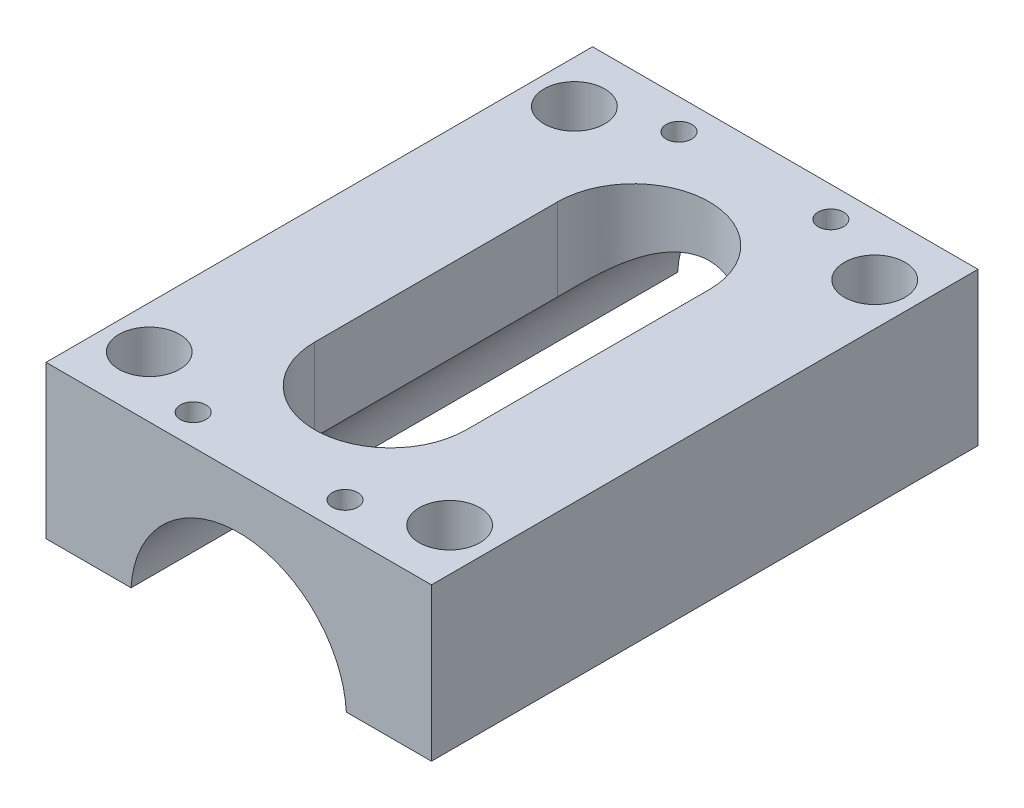
SolidWorks part; units mm, degrees
ref_plane "Front" through (0, 0, 0) normal (0, 0, 1) x (1, 0, 0)
ref_plane "Top" through (0, 0, 0) normal (0, 1, 0) x (1, 0, 0)
ref_plane "Right" through (0, 0, 0) normal (1, 0, 0) x (0, 0, -1)
sketch "Sketch1" plane through (0, 0, 0) normal (0, 0, 1) x (1, 0, 0)
  line L0 (-31.75, 0) -> (31.75, 0) construction
  line L1 (-31.7342, 1) -> (-17.7218, 1)
  line L2 (-31.75, 1) -> (31.75, 1) construction
  line L3 (17.7218, 1) -> (31.7342, 1)
  arc A0 (31.7342, 1) -> (-31.7342, 1) centre (0, 0) ccw
  arc A1 (17.7218, 1) -> (-17.7218, 1) centre (0, 0) ccw
  dimension "D1" = 35.5
  dimension "D2" = 63.5
  dimension "D3" = 1
extrude "Boss-Extrude1" add sketch "Sketch1" along normal blind 90
sketch "Sketch12" plane through (0, 0, 90) normal (0, 0, 1) x (1, 0, 0)
  line L2 (-31.7342, 1) -> (-31.7342, 31.75)
  line L3 (-31.7342, 31.75) -> (31.7342, 31.75)
  line L4 (31.7342, 1) -> (31.7342, 31.75)
  arc A0 (31.7342, 1) -> (-31.7342, 1) centre (0, 0) ccw construction
  arc A1 (31.7342, 1) -> (-31.7342, 1) centre (0, 0) ccw
  point P4 (0, 16.375)
  point P9 (0, 0)
  arc M5 (31.7342, 1) -> (-31.7342, 1) centre (0, 0) ccw
extrude "Boss-Extrude2" add sketch "Sketch12" against normal up to surface (90 mm away) contours L4 L3 M5 | L3 L2 M5 up to face at (0, 12.875, 0)
sketch "Sketch2" plane through (0, 1, 0) normal (0, -1, 0) x (-1, 0, 0)
  line L0 (24.728, -90) -> (24.728, 0) construction
  line L1 (31.7342, -90) -> (17.7218, -90) construction
  line L2 (31.7342, 0) -> (17.7218, 0) construction
  line L3 (-24.728, -90) -> (-24.728, 0) construction
  line L4 (-17.7218, -90) -> (-31.7342, -90) construction
  line L5 (-17.7218, 0) -> (-31.7342, 0) construction
  line L6 (0, -90) -> (0, 0) construction
  line L7 (-17.7218, -90) -> (17.7218, -90) construction
  circle A0 centre (24.728, -80) radius 1
  circle A1 centre (24.728, -10) radius 1
  circle A2 centre (-24.728, -10) radius 1
  circle A3 centre (-24.728, -80) radius 1
  dimension "D1" = 10
  dimension "D2" = 10
  dimension "D3" = 2
hole_wizard "Ø5.0mm Clearance Dowel Hole1" positions "3DSketch1" profile "Sketch3" hole size "Ø5.0" standard "ANSI Metric" end condition up to next
sketch3d "3DSketch1"
  point P0 (-24.728, 1, 80)
  point P3 (-24.728, 1, 10)
  point P6 (24.728, 1, 80)
  point P9 (24.728, 1, 10)
sketch "Sketch3" plane through (-24.728, 1, 80) normal (1, 0, 0) x (0, 0, -1)
  line L0 (0, 0) -> (0, 30.75)
  line L1 (0, 30.75) -> (2.5, 30.75)
  line L2 (2.5, 30.75) -> (2.5, 0)
  line L5 (2.5, 0) -> (0, 0)
  line L11 (0, -6.35) -> (0, 107.95) construction
  dimension "Thru Hole Dia." = 5
  dimension "Thru Hole Depth" = 30.75
ref_plane "Plane1" through (0, 4, 0) normal (0, -1, 0) x (-1, 0, 0)
sketch "Sketch4" plane through (0, 4, 0) normal (0, -1, 0) x (-1, 0, 0)
  circle A0 centre (24.728, -80) radius 5
  circle A1 centre (24.728, -10) radius 5
  circle A2 centre (-24.728, -10) radius 5
  circle A3 centre (-24.728, -80) radius 5
  dimension "D1" = 10
extrude "Cut-Extrude1" cut sketch "Sketch4" against normal up to next
sketch "Sketch8" plane through (0, 0, 90) normal (0, 0, 1) x (1, 0, 0)
  line L0 (18, 26.1546) -> (-18, 26.1546)
  line L1 (-31.7342, 26.1546) -> (31.7342, 26.1546)
  line L2 (-31.7342, 1) -> (-31.7342, 31.75) construction
  line L3 (31.7342, 1) -> (31.7342, 31.75) construction
  line L4 (31.7342, 26.1546) -> (31.7342, 31.75)
  line L5 (31.7342, 31.75) -> (-31.7342, 31.75)
  line L6 (-31.7342, 31.75) -> (31.7342, 31.75) construction
  line L7 (-31.7342, 31.75) -> (-31.7342, 26.1546)
  arc A1 (18, 26.1546) -> (-18, 26.1546) centre (0, 0) ccw
  line M7 (31.7342, 1) -> (31.7342, 31.75)
  line M8 (31.7342, 31.75) -> (-31.7342, 31.75)
  line M9 (-31.7342, 31.75) -> (-31.7342, 1)
  dimension "D1" = 36
extrude "Cut-Extrude3" cut sketch "Sketch8" against normal through all contours A1 L5 L1 M9 | L0 A1 | A1 L1 M7 M8
sketch "Sketch9" plane through (0, 1, 0) normal (0, -1, 0) x (1, 0, 0)
  line L0 (0, 25) -> (0, 65) construction
  line L1 (0, 90) -> (0, 0) construction
  line L2 (-12.5, 25) -> (-12.5, 65)
  line L3 (12.5, 25) -> (12.5, 65)
  arc A0 (-12.5, 25) -> (12.5, 25) centre (0, 25) ccw
  arc A1 (12.5, 65) -> (-12.5, 65) centre (0, 65) ccw
  point P4 (0, 45)
  dimension "D1" = 25
  dimension "D2" = 40
extrude "Cut-Extrude4" cut sketch "Sketch9" against normal up to next
sketch "Sketch10" plane through (0, 26.1546, 0) normal (0, 1, 0) x (1, 0, 0)
  line L0 (0, -90) -> (0, 0) construction
  line L1 (-12.5, -85) -> (12.5, -85) construction
  line L2 (-12.5, -85) -> (-12.5, -5) construction
  line L3 (-12.5, -5) -> (12.5, -5) construction
  line L4 (12.5, -85) -> (12.5, -5) construction
  line L5 (-12.5, -85) -> (12.5, -5) construction
  line L6 (-12.5, -5) -> (12.5, -85) construction
  circle A0 centre (12.5, -5) radius 2.5
  circle A1 centre (-12.5, -5) radius 2.5
  circle A2 centre (12.5, -85) radius 2.5
  circle A3 centre (-12.5, -85) radius 2.5
  point P0 (0, -45)
  dimension "D1" = 5
  dimension "D2" = 80
  dimension "D3" = 25
hole_wizard "Tap Drill for M5x0.8 Tap1" positions "3DSketch2" profile "Sketch11" hole size "M5x0.8" standard "ANSI Metric"
sketch3d "3DSketch2"
  point P0 (-12.5, 26.1546, 5)
  point P3 (12.5, 26.1546, 5)
  point P6 (12.5, 26.1546, 85)
  point P9 (-12.5, 26.1546, 85)
sketch "Sketch11" plane through (-12.5, 26.1546, 5) normal (1, 0, 0) x (0, 0, 1)
  line L0 (0, 0) -> (0, 9.2618)
  line L1 (0, 9.2618) -> (2.1, 8)
  line L2 (2.1, 8) -> (2.1, 0)
  line L5 (2.1, 0) -> (0, 0)
  line L10 (0, 9.2618) -> (-2.1, 8) construction
  line L11 (0, -6.35) -> (0, 107.95) construction
  dimension "Hole Dia." = 4.2
  dimension "Hole Depth" = 8
  dimension "Drill Angle" = 118
